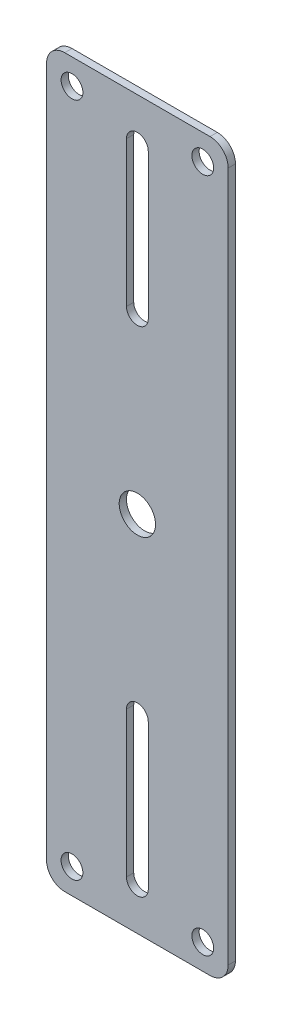
SolidWorks part; units mm, degrees
ref_plane "Piano frontale" through (0, 0, 0) normal (0, 0, 1) x (1, 0, 0)
ref_plane "Piano superiore" through (0, 0, 0) normal (0, 1, 0) x (1, 0, 0)
ref_plane "Piano destro" through (0, 0, 0) normal (1, 0, 0) x (0, 0, -1)
sketch "Schizzo1" plane through (0, 0, 0) normal (0, 0, 1) x (1, 0, 0)
  line L0 (-3, 88) -> (-3, 48)
  line L1 (-25, 100) -> (25, 100)
  line L2 (-25, 100) -> (-25, 0)
  line L3 (-25, 0) -> (25, 0)
  line L4 (25, 100) -> (25, 0)
  line L5 (3, 48) -> (3, 88)
  circle A0 centre (-18, 93) radius 3
  circle A1 centre (18, 93) radius 3
  arc A2 (-3, 48) -> (3, 48) centre (0, 48) ccw
  arc A3 (3, 88) -> (-3, 88) centre (0, 88) ccw
  point P5 (0, 0)
  dimension "D3" = 6
  dimension "D4" = 6
  dimension "D8" = 7
  dimension "D10" = 46
  dimension "D11" = 9
  dimension "D1" = 50
  dimension "D2" = 100
  dimension "D5" = 7
  dimension "D6" = 7
  dimension "D7" = 7
  dimension "D9" = 6
extrude "Estrusione-Estrusione1" add sketch "Schizzo1" along normal blind 2
fillet "Raccordo3" radius 5 1 edges at (25, 100, 1)
fillet "Raccordo4" radius 5 1 edges at (-25, 100, 1)
mirror "Specchia1" about plane through (-25, 0, 2) normal (0, 1, 0) of bodies 101
sketch "Schizzo3" plane through (0, 0, 2) normal (0, 0, 1) x (1, 0, 0)
  circle A0 centre (0, 0) radius 5
  dimension "D1" = 10
extrude "Taglio-Estrusione1" cut sketch "Schizzo3" against normal through all
